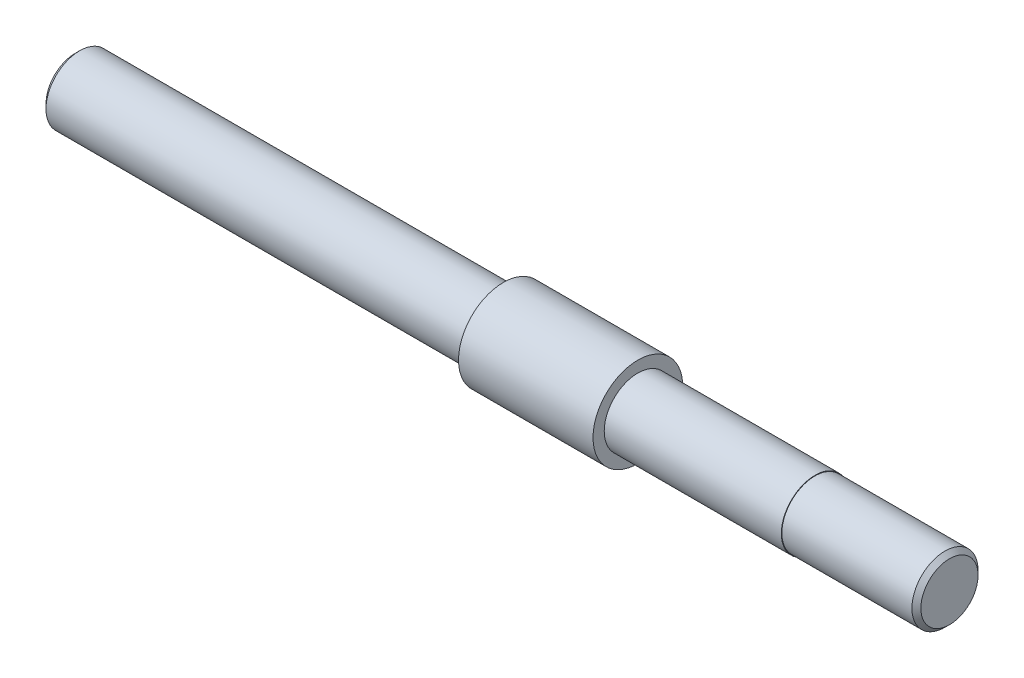
SolidWorks part; units mm, degrees
ref_plane "前视基准面" through (0, 0, 0) normal (0, 0, 1) x (1, 0, 0)
ref_plane "上视基准面" through (0, 0, 0) normal (0, 1, 0) x (1, 0, 0)
ref_plane "右视基准面" through (0, 0, 0) normal (1, 0, 0) x (0, 0, -1)
sketch "草图1" plane through (0, 0, 0) normal (0, 0, 1) x (1, 0, 0)
  line L0 (-12.0888, 0) -> (5.2383, 0) construction
  line L1 (0, 9.0788) -> (0, -9.2095) construction
  line L2 (0, 0) -> (0, 1.475)
  line L3 (0, 1.475) -> (-6, 1.475)
  line L4 (-6, 1.475) -> (-6, 1.5)
  line L5 (-6, 1.5) -> (-13.9, 1.5)
  line L6 (-13.9, 1.5) -> (-13.9, 2)
  line L7 (-13.9, 2) -> (-19.9, 2)
  line L8 (-19.9, 2) -> (-19.9, 1.5)
  line L9 (-19.9, 1.5) -> (-39, 1.5)
  line L10 (-39, 1.5) -> (-39, 0)
  line L11 (-39, 0) -> (0, 0)
  dimension "D1" = 2.95
  dimension "D2" = 3
  dimension "D3" = 3
  dimension "D4" = 4
  dimension "D5" = 6
  dimension "D6" = 13.9
  dimension "D7" = 39
  dimension "D8" = 6
revolve "旋转1" add sketch "草图1" angle 360 about L0
cosmetic thread "装饰螺纹线1" parameters "D2"=2.013
chamfer "倒角1" distance 0.2 angle 45 2 edges at (-39, 0, 1.5) (0, 0, 1.475)
